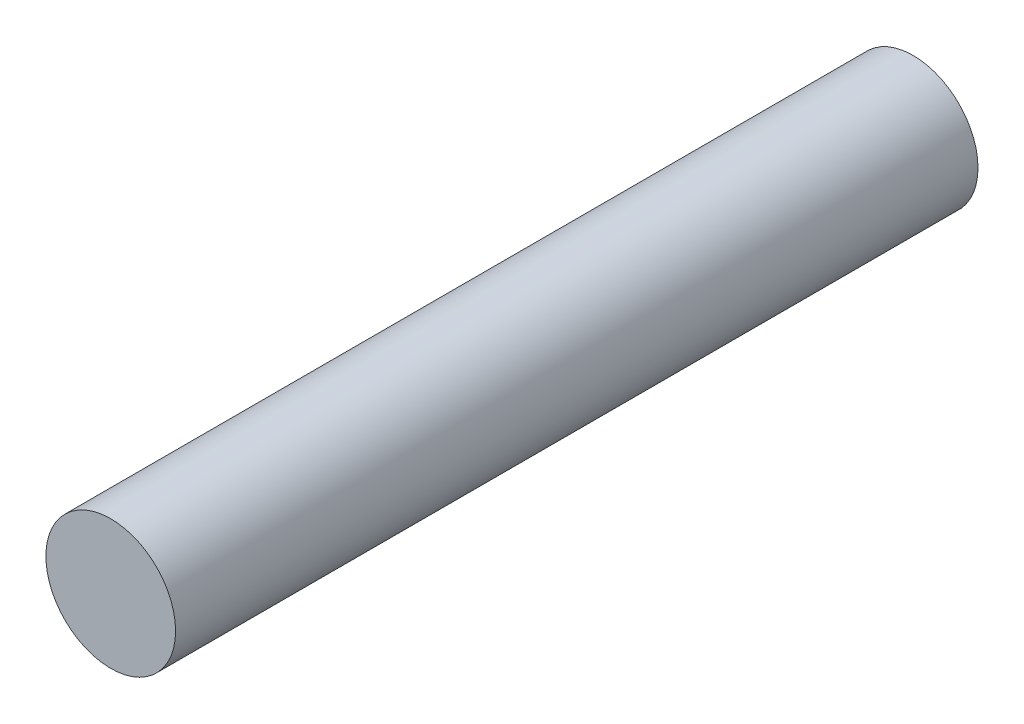
SolidWorks part; units mm, degrees
ref_plane "Front Plane" through (0, 0, 0) normal (0, 0, 1) x (1, 0, 0)
ref_plane "Top Plane" through (0, 0, 0) normal (0, 1, 0) x (1, 0, 0)
ref_plane "Right Plane" through (0, 0, 0) normal (1, 0, 0) x (0, 0, -1)
sketch "Sketch1" plane through (0, 0, 0) normal (0, 0, 1) x (1, 0, 0)
  circle A0 centre (0, 0) radius 26.67
  dimension "D1" = 53.34
extrude "Boss-Extrude1" add sketch "Sketch1" along normal blind 330
